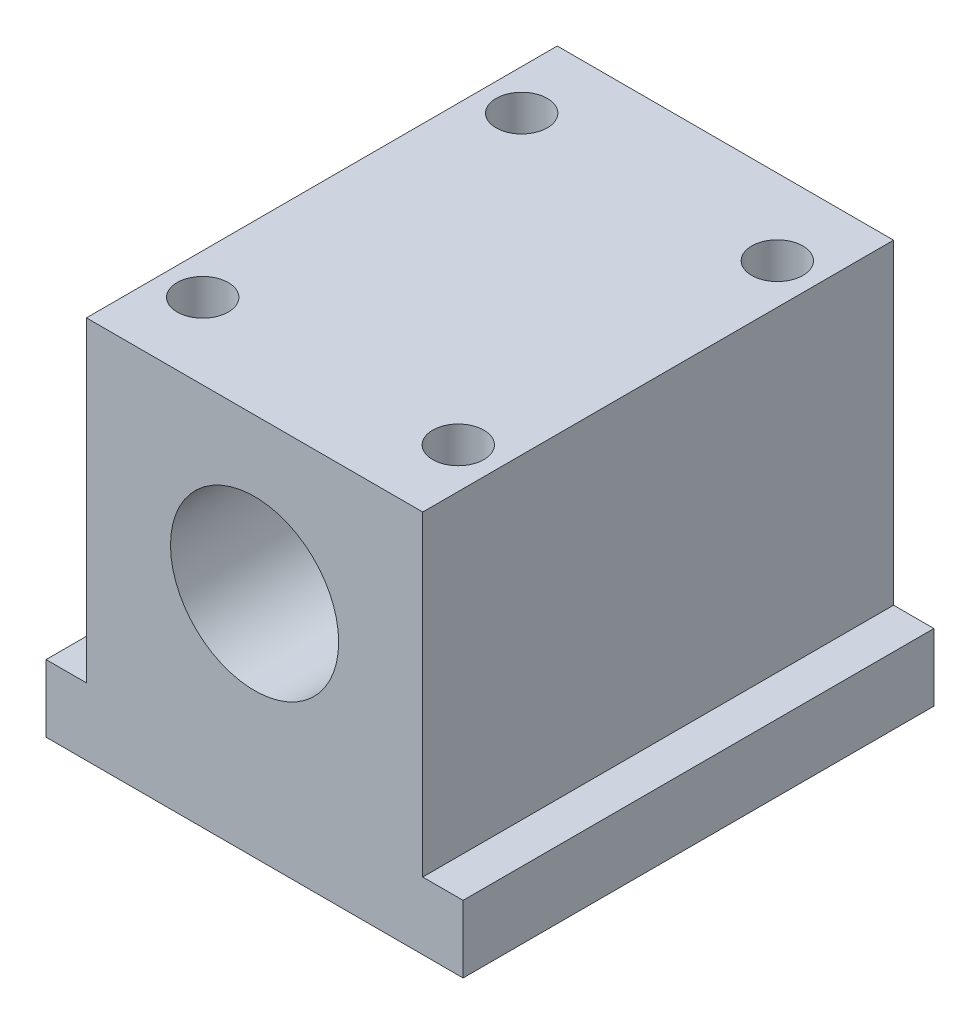
SolidWorks part; units mm, degrees
ref_plane "Front Plane" through (0, 0, 0) normal (0, 0, 1) x (1, 0, 0)
ref_plane "Top Plane" through (0, 0, 0) normal (0, 1, 0) x (1, 0, 0)
ref_plane "Right Plane" through (0, 0, 0) normal (1, 0, 0) x (0, 0, -1)
sketch "Sketch1" plane through (0, 0, 0) normal (0, 0, 1) x (1, 0, 0)
  line L0 (0, 24.0346) -> (0, -24.0346) construction
  line L1 (25, -19.0346) -> (31, -19.0346)
  line L2 (-31, -29.0346) -> (31, -29.0346)
  line L3 (-31, -29.0346) -> (-31, -19.0346)
  line L4 (-31, -19.0346) -> (-25, -19.0346)
  line L5 (31, -29.0346) -> (31, -19.0346)
  line L8 (-25, 27.9654) -> (25, 27.9654)
  line L9 (-25, 27.9654) -> (-25, -19.0346)
  line L11 (25, 27.9654) -> (25, -19.0346)
  circle A0 centre (0, 4.9654) radius 12.5
  point P4 (0, 0)
  point P9 (0, 0)
  dimension "D6" = 25
  dimension "D1" = 62
  dimension "D2" = 10
  dimension "D3" = 50
  dimension "D4" = 23
  dimension "D5" = 47
extrude "Boss-Extrude1" add sketch "Sketch1" along normal blind 70
sketch "Sketch2" plane through (0, 27.9654, 0) normal (0, 1, 0) x (1, 0, 0)
  line L0 (0, 0) -> (0, -70) construction
  line L1 (25, -70) -> (-25, -70) construction
  line L2 (0, -35) -> (25, -35) construction
  line L3 (25, -70) -> (25, 0) construction
  circle A0 centre (19, -58.7146) radius 3.805
  circle A1 centre (-19, -58.7146) radius 3.805
  dimension "D1" = 11.2854
  dimension "D2" = 19
extrude "Cut-Extrude1" cut sketch "Sketch2" against normal blind 23
sketch "Sketch3" plane through (0, 27.9654, 0) normal (0, 1, 0) x (1, 0, 0)
  circle A2 centre (19, -11.2854) radius 3.805
  circle A3 centre (-19, -11.2854) radius 3.805
extrude "Cut-Extrude2" cut sketch "Sketch3" against normal blind 12
